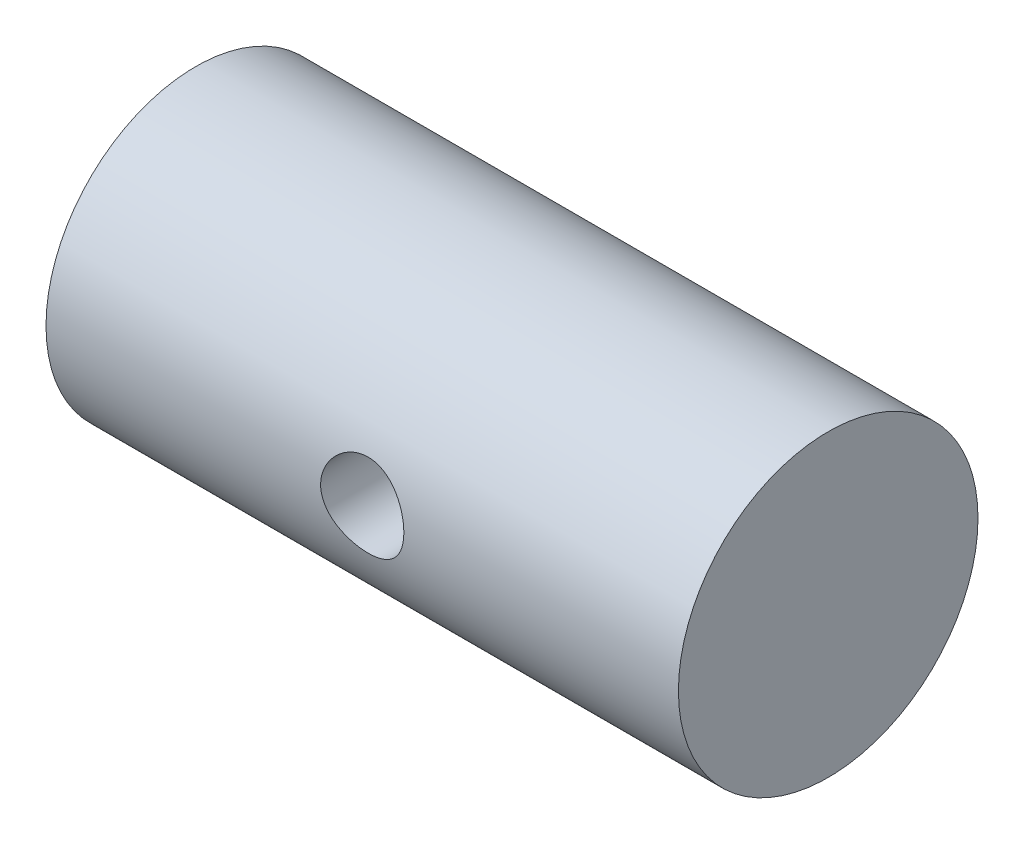
SolidWorks part; units mm, degrees
material "1.0050 (E295)"
ref_plane "Płaszczyzna przednia" through (0, 0, 0) normal (0, 0, 1) x (1, 0, 0)
ref_plane "Płaszczyzna górna" through (0, 0, 0) normal (0, 1, 0) x (1, 0, 0)
ref_plane "Płaszczyzna prawa" through (0, 0, 0) normal (1, 0, 0) x (0, 0, -1)
sketch "Szkic1" plane through (0, 0, 0) normal (1, 0, 0) x (0, 0, -1)
  circle A0 centre (0, 0) radius 9
  dimension "D1" = 18
extrude "Dodanie-wyciągnięcie1" add sketch "Szkic1" along normal blind 38
ref_plane "Płaszczyzna2" through (19, 0, 0) normal (1, 0, 0) x (0, 0, -1)
sketch "Szkic2" plane through (0, 0, 0) normal (0, 0, 1) x (1, 0, 0)
  line L0 (38, -9) -> (38, 9) construction
  circle A0 centre (19, 0) radius 2.5
  point P4 (0, 0)
  dimension "D1" = 5
  dimension "D2" = 19
extrude "Wytnij-wyciągnięcie1" cut sketch "Szkic2" against normal up to next and the other way up to next
